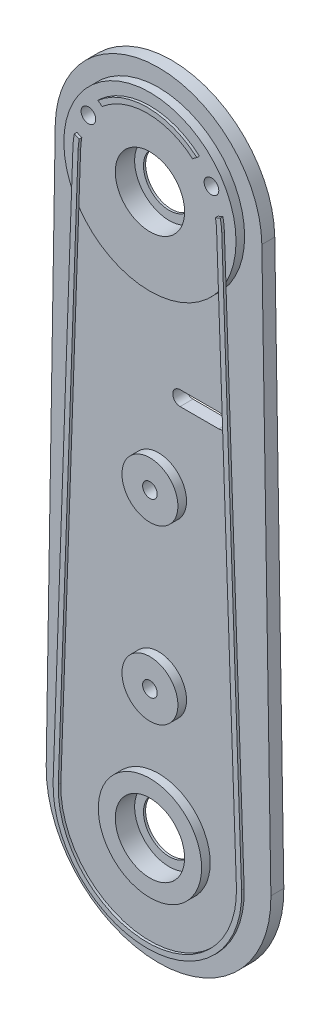
SolidWorks part; units mm, degrees
ref_plane "Front Plane" through (0, 0, 0) normal (0, 0, 1) x (1, 0, 0)
ref_plane "Top Plane" through (0, 0, 0) normal (0, 1, 0) x (1, 0, 0)
ref_plane "Right Plane" through (0, 0, 0) normal (1, 0, 0) x (0, 0, -1)
ref_plane "Plane1" through (0, 0, 328.5) normal (0, 0, 1) x (1, 0, 0)
sketch "Sketch1" plane through (0, 0, 328.5) normal (0, 0, 1) x (1, 0, 0)
  line L0 (276.0031, 300.3874) -> (273.9048, 170.4213)
  line L1 (326.0952, 170.4213) -> (323.9969, 300.3874)
  line L2 (305, 258.3) -> (314, 258.3)
  line L3 (314, 261.7) -> (305, 261.7)
  arc A0 (273.9048, 170.4213) -> (326.0952, 170.4213) centre (300, 170) ccw
  arc A1 (323.9969, 300.3874) -> (276.0031, 300.3874) centre (300, 300) ccw
  circle A2 centre (300, 300) radius 6
  circle A3 centre (300, 170) radius 6
  arc A4 (314, 258.3) -> (314, 261.7) centre (314, 260) ccw
  arc A5 (305, 261.7) -> (305, 258.3) centre (305, 260) ccw
  circle A6 centre (314.2894, 308.25) radius 1.7
  circle A7 centre (285.7106, 308.25) radius 1.7
  circle A8 centre (300, 240) radius 1.7
  circle A9 centre (300, 200) radius 1.7
extrude "Boss-Extrude1" add sketch "Sketch1" along normal blind 3
ref_plane "Plane2" through (0, 0, 331.5) normal (0, 0, 1) x (1, 0, 0)
sketch "Sketch2" plane through (0, 0, 331.5) normal (0, 0, 1) x (1, 0, 0)
  circle A0 centre (300, 300) radius 20
  circle A1 centre (300, 300) radius 6
  circle A2 centre (314.2894, 308.25) radius 1.7
  circle A3 centre (285.7106, 308.25) radius 1.7
extrude "Boss-Extrude2" add sketch "Sketch2" along normal blind 2
sketch "Sketch3" plane through (0, 0, 331.5) normal (0, 0, 1) x (1, 0, 0)
  circle A0 centre (300, 170) radius 12
  circle A1 centre (300, 170) radius 6
extrude "Boss-Extrude3" add sketch "Sketch3" along normal blind 2
sketch "Sketch4" plane through (0, 0, 331.5) normal (0, 0, 1) x (1, 0, 0)
  circle A0 centre (300, 240) radius 6.5
  circle A1 centre (300, 240) radius 1.7
extrude "Boss-Extrude4" add sketch "Sketch4" along normal blind 2
sketch "Sketch5" plane through (0, 0, 331.5) normal (0, 0, 1) x (1, 0, 0)
  circle A0 centre (300, 200) radius 6.5
  circle A1 centre (300, 200) radius 1.7
extrude "Boss-Extrude5" add sketch "Sketch5" along normal blind 2
ref_plane "Plane3" through (0, 0, 333.5) normal (0, 0, 1) x (1, 0, 0)
sketch "Sketch6" plane through (0, 0, 333.5) normal (0, 0, 1) x (1, 0, 0)
  line L0 (282.7108, 300.612) -> (278.1151, 170.7746)
  line L1 (321.8849, 170.7746) -> (317.2892, 300.612)
  line L2 (283.9101, 300.5695) -> (279.3144, 170.7322)
  line L3 (320.6856, 170.7322) -> (316.0899, 300.5695)
  arc A0 (278.1151, 170.7746) -> (321.8849, 170.7746) centre (300, 170) ccw
  arc A1 (317.2892, 300.612) -> (282.7108, 300.612) centre (300, 300) ccw
  arc A2 (279.3144, 170.7322) -> (320.6856, 170.7322) centre (300, 170) ccw
  arc A3 (316.0899, 300.5695) -> (283.9101, 300.5695) centre (300, 300) ccw
extrude "Boss-Extrude6" add sketch "Sketch6" along normal blind 0.6
sketch "Sketch7" plane through (0, 0, 333.5) normal (0, 0, 1) x (1, 0, 0)
  circle A0 centre (314.2894, 308.25) radius 5.45
  circle A1 centre (285.7106, 308.25) radius 5.45
extrude "Cut-Extrude1" cut sketch "Sketch7" along normal blind 0.6
ref_plane "Plane4" through (0, 0, 329) normal (0, 0, 1) x (1, 0, 0)
sketch "Sketch8" plane through (0, 0, 329) normal (0, 0, 1) x (1, 0, 0)
  circle A0 centre (300, 300) radius 8.05
  circle A1 centre (300, 170) radius 8.05
extrude "Cut-Extrude2" cut sketch "Sketch8" along normal blind 4.5
sketch "Sketch9" plane through (0, 0, 328.5) normal (0, 0, 1) x (1, 0, 0)
  circle A0 centre (314.2894, 308.25) radius 3.75
  circle A1 centre (285.7106, 308.25) radius 3.75
  circle A2 centre (300, 240) radius 3.75
  circle A3 centre (300, 200) radius 3.75
extrude "Cut-Extrude3" cut sketch "Sketch9" along normal blind 2.3
